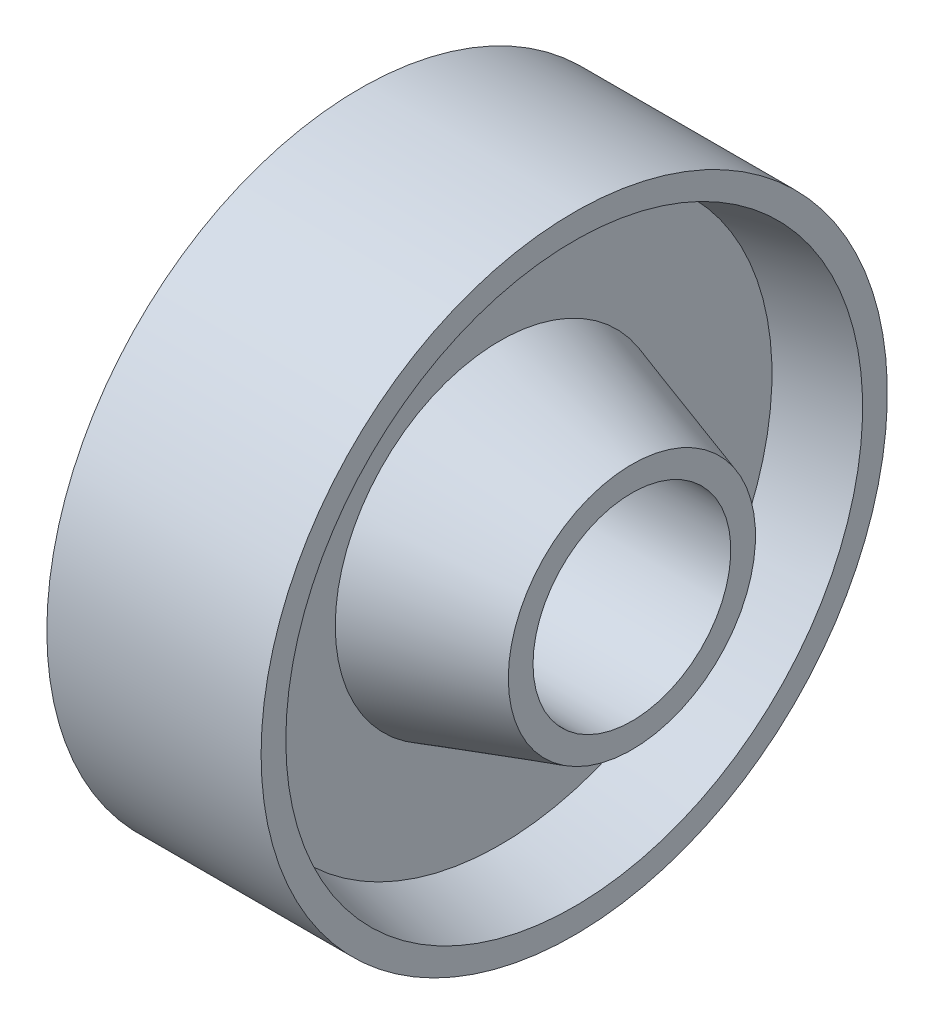
SolidWorks part; units mm, degrees
ref_plane "Front Plane" through (0, 0, 0) normal (0, 0, 1) x (1, 0, 0)
ref_plane "Top Plane" through (0, 0, 0) normal (0, 1, 0) x (1, 0, 0)
ref_plane "Right Plane" through (0, 0, 0) normal (1, 0, 0) x (0, 0, -1)
sketch "Sketch1" plane through (0, 0, 0) normal (0, 0, 1) x (1, 0, 0)
  line L0 (0, 0) -> (21.9648, 0) construction
  line L1 (0, 0) -> (0, 38) construction
  line L2 (20, 12) -> (-20, 12)
  line L3 (-20, 12) -> (-20, 15)
  line L4 (-20, 15) -> (-4, 20)
  line L5 (-4, 20) -> (-4, 33)
  line L6 (-4, 33) -> (-13, 35)
  line L7 (-13, 35) -> (-13, 38)
  line L8 (-13, 38) -> (13, 38)
  line L9 (20, 12) -> (20, 15)
  line L10 (20, 15) -> (4, 20)
  line L11 (4, 20) -> (4, 33)
  line L12 (4, 33) -> (13, 35)
  line L13 (13, 35) -> (13, 38)
  point P6 (0, 0)
  point P12 (0, 0)
  point P14 (0, 12)
  dimension "D1" = 26
  dimension "D2" = 40
  dimension "D3" = 8
  dimension "D4" = 12
  dimension "D5" = 15
  dimension "D6" = 20
  dimension "D7" = 33
  dimension "D8" = 35
  dimension "D9" = 38
revolve "Revolve1" add sketch "Sketch1" angle 360 about L0
